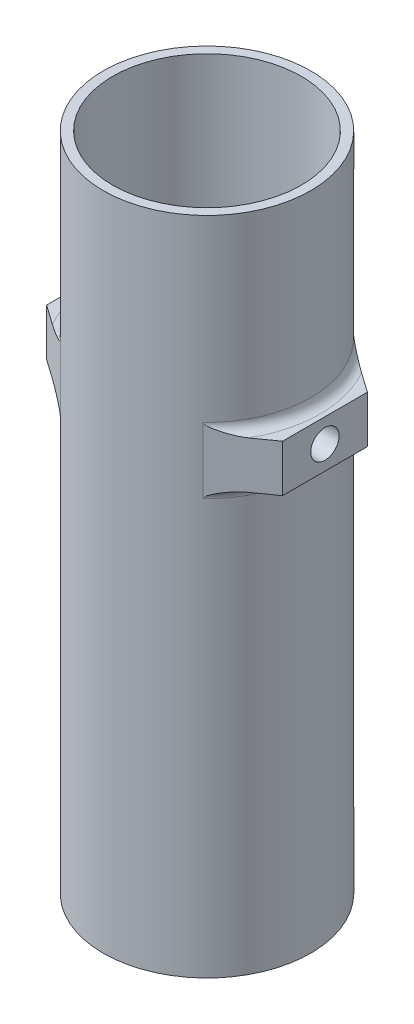
SolidWorks part; units mm, degrees
ref_plane "Alzado" through (0, 0, 0) normal (0, 0, 1) x (1, 0, 0)
ref_plane "Planta" through (0, 0, 0) normal (0, 1, 0) x (1, 0, 0)
ref_plane "Vista lateral" through (0, 0, 0) normal (1, 0, 0) x (0, 0, -1)
sketch "Croquis1" plane through (0, 0, 0) normal (0, 1, 0) x (1, 0, 0)
  circle A0 centre (0, 0) radius 10
  circle A1 centre (0, 0) radius 11
  dimension "D1" = 20
  dimension "D2" = 1
extrude "Saliente-Extruir1" add sketch "Croquis1" along normal blind 70
ref_plane "Plano1" through (0, 50, 0) normal (0, 1, 0) x (1, 0, 0)
sketch "Croquis2" plane through (0, 50, 0) normal (0, 1, 0) x (1, 0, 0)
  line L0 (-12.5, -4.5) -> (-12.5, 4.5)
  line L1 (-12.5, 4.5) -> (-4.9867, 9.8047)
  line L2 (-12.5, -12.5) -> (12.5, -12.5) construction
  line L3 (-12.5, -12.5) -> (-12.5, 12.5) construction
  line L4 (-12.5, 12.5) -> (12.5, 12.5) construction
  line L5 (12.5, -12.5) -> (12.5, 12.5) construction
  line L6 (-12.5, -12.5) -> (0, 0) construction
  line L7 (-12.5, 12.5) -> (0, 0) construction
  line L8 (-12.5, -4.5) -> (-4.9867, -9.8047)
  line L9 (7.7782, 7.7782) -> (12.5, 12.5) construction
  line L10 (7.7782, -7.7782) -> (12.5, -12.5) construction
  line L11 (0, 0) -> (0, 10) construction
  line L12 (12.5, 4.5) -> (4.9867, 9.8047)
  line L13 (12.5, -4.5) -> (12.5, 4.5)
  line L14 (12.5, -4.5) -> (4.9867, -9.8047)
  circle A0 centre (0, 0) radius 11 construction
  arc A1 (-4.9867, 9.8047) -> (-4.9867, -9.8047) centre (0, 0) ccw
  arc A2 (7.7782, -7.7782) -> (7.7782, 7.7782) centre (0, 0) ccw
  circle A3 centre (0, 0) radius 10 construction
  arc A4 (4.9867, 9.8047) -> (4.9867, -9.8047) centre (0, 0) cw
  point P6 (-12.5, 0)
  dimension "D1" = 9
  dimension "D2" = 25
  dimension "D3" = 25
extrude "Saliente-Extruir2" add sketch "Croquis2" against normal blind 5 contours A1 L1 L0 L8 | L12 A4 A2 L14 L13
sketch "Croquis3" plane through (-12.5, 0, 0) normal (-1, 0, 0) x (0, 0, 1)
  line L0 (0, 45) -> (0, 50) construction
  line L1 (4.5, 45) -> (-4.5, 45) construction
  line L2 (7.9805, 50) -> (-7.9805, 50) construction
  circle A0 centre (0, 47.5) radius 1.5
  dimension "D1" = 3
extrude "Cortar-Extruir1" cut sketch "Croquis3" against normal through all both and the other way through all contours A0 L0
fillet "Redondeo1" radius 1 4 edges at (11, 45, 0) (-11, 45, 0) (11, 50, 0) (-11, 50, 0)
sketch "Croquis4" plane through (0, 0, 0) normal (1, 0, 0) x (0, 0, -1)
  line L0 (0, 66.5) -> (0, 70) construction
  line L1 (11, 70) -> (-11, 70) construction
  circle A0 centre (0, 66.5) radius 1.5
  circle A1 centre (0, 66.5) radius 2.5
  dimension "D1" = 3
  dimension "D2" = 3.5
  dimension "D3" = 1
extrude "Saliente-Extruir3" add sketch "Croquis4" against normal blind 1.4 from offset 10.5
